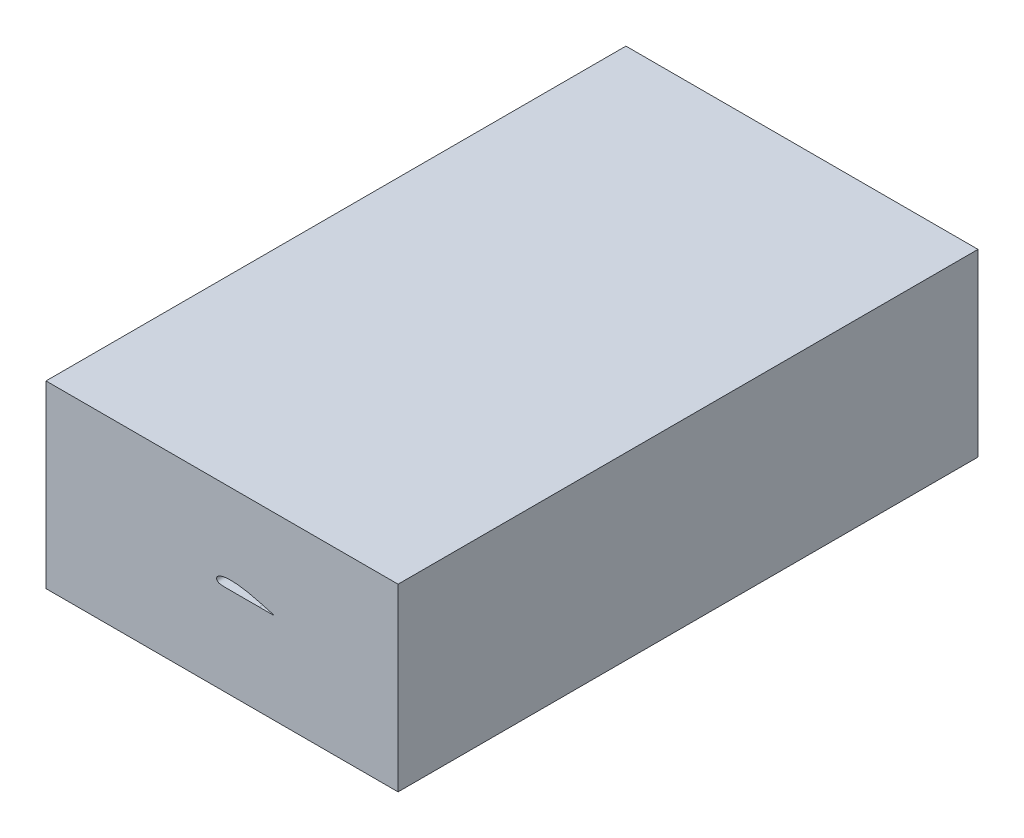
SolidWorks part; units mm, degrees
ref_plane "Front Plane" through (0, 0, 0) normal (0, 0, 1) x (1, 0, 0)
ref_plane "Top Plane" through (0, 0, 0) normal (0, 1, 0) x (1, 0, 0)
ref_plane "Right Plane" through (0, 0, 0) normal (1, 0, 0) x (0, 0, -1)
sketch "Sketch1" plane through (0, 0, 0) normal (0, 0, 1) x (1, 0, 0)
  line L0 (441.3938, 20.1125) -> (470.7202, 20.1125) construction
  line L1 (470.8525, 21.0946) -> (442.557, 28.8563) construction
  line L2 (441.3938, 20.1125) -> (470.7202, 20.1125)
  line L3 (470.8525, 21.0946) -> (442.557, 28.8563)
  line L5 (0, 204.6763) -> (728.5077, 204.6763)
  line L6 (0, 204.6763) -> (0, -167.5714)
  line L7 (0, -167.5714) -> (728.5077, -167.5714)
  line L8 (728.5077, 204.6763) -> (728.5077, -167.5714)
  arc A0 (470.7202, 20.1125) -> (470.8525, 21.0946) centre (470.7202, 20.6125) ccw construction
  arc A1 (470.7202, 20.1125) -> (470.8525, 21.0946) centre (470.7202, 20.6125) ccw
  spline S0 degree 3 poles (1124.9258, 3617.1089) (1623.2842, 17.455) (1021.1685, 21.1727) (419.9315, 20.0736) (410.9894, 20.058) (403.8355, 20.0448) (398.4705, 20.035) (393.1045, 20.0244) (387.735, 20.0177) (383.2749, 20.0094) (379.6961, 19.9964) (376.991, 19.9944) (374.2712, 20.0109) (371.5307, 20.0564) (369.229, 20.1314) (367.3787, 20.22) (365.9782, 20.3046) (364.5787, 20.4101) (363.214, 20.5264) (361.9719, 20.652) (360.9049, 20.8056) (360.0698, 20.9562) (359.288, 21.1303) (358.6401, 21.281) (357.7655, 21.5068) (356.8397, 21.8718) (356.056, 22.2868) (355.3251, 22.8111) (354.7889, 23.3017) (354.3478, 23.793) (353.9982, 24.2624) (353.6956, 24.7529) (353.3653, 25.4506) (353.1116, 26.2983) (352.9613, 27.6499) (353.2277, 28.9329) (353.5863, 29.7672) (353.965, 30.4492) (354.39, 31.0256) (354.8557, 31.5528) (355.3545, 32.0442) (355.8208, 32.4753) (356.5526, 33.1031) (357.3891, 33.7069) (358.2164, 34.2146) (359.2877, 34.7841) (360.5728, 35.3529) (362.0564, 35.8958) (363.4799, 36.3495) (364.9084, 36.7539) (366.8278, 37.2314) (369.2107, 37.707) (372.0662, 38.14) (374.9635, 38.4319) (378.7767, 38.631) (383.377, 38.6454) (388.8653, 38.5359) (394.4128, 38.2045) (401.7202, 37.4887) (410.7798, 36.1975) (421.4868, 34.1106) (594.8285, -5.7248) (705.5133, -179.2585) (3213.2276, 2881.47) knots -10.317793 -10.317793 -10.317793 -10.317793 0.062498 0.124997 0.187495 0.218745 0.249994 0.281243 0.312492 0.343742 0.359366 0.374991 0.390615 0.40624 0.421865 0.429677 0.437489 0.445302 0.453114 0.460926 0.464832 0.468739 0.472645 0.476551 0.480457 0.48241 0.484363 0.486316 0.488269 0.489246 0.490222 0.491199 0.492175 0.493152 0.494129 0.496082 0.497058 0.498035 0.499988 0.501941 0.503894 0.5078 0.511706 0.515612 0.519519 0.523425 0.531237 0.539049 0.546862 0.554674 0.562486 0.578111 0.593736 0.60936 0.624985 0.656234 0.687483 0.718732 0.749982 0.81248 0.874979 0.937477 3.874805 3.874805 3.874805 3.874805 only from (441.3938, 20.1125) to (442.557, 28.8563) construction
  spline S1 degree 3 poles (441.3938, 20.1125) (437.8166, 20.1056) (430.6622, 20.0933) (419.9315, 20.0736) (410.9894, 20.058) (403.8355, 20.0448) (398.4705, 20.035) (393.1045, 20.0244) (387.735, 20.0177) (383.2749, 20.0094) (379.6961, 19.9964) (376.991, 19.9944) (374.2712, 20.0109) (371.5307, 20.0564) (369.229, 20.1314) (367.3787, 20.22) (365.9782, 20.3046) (364.5787, 20.4101) (363.214, 20.5264) (361.9719, 20.652) (360.9049, 20.8056) (360.0698, 20.9562) (359.288, 21.1303) (358.6401, 21.281) (357.7655, 21.5068) (356.8397, 21.8718) (356.056, 22.2868) (355.3251, 22.8111) (354.7889, 23.3017) (354.3478, 23.793) (353.9982, 24.2624) (353.6956, 24.7529) (353.3653, 25.4506) (353.1116, 26.2983) (352.9613, 27.6499) (353.2277, 28.9329) (353.5863, 29.7672) (353.965, 30.4492) (354.39, 31.0256) (354.8557, 31.5528) (355.3545, 32.0442) (355.8208, 32.4753) (356.5526, 33.1031) (357.3891, 33.7069) (358.2164, 34.2146) (359.2877, 34.7841) (360.5728, 35.3529) (362.0564, 35.8958) (363.4799, 36.3495) (364.9084, 36.7539) (366.8278, 37.2314) (369.2107, 37.707) (372.0662, 38.14) (374.9635, 38.4319) (378.7767, 38.631) (383.377, 38.6454) (388.8653, 38.5359) (394.4128, 38.2045) (401.7202, 37.4887) (410.7798, 36.1975) (421.4868, 34.1106) (432.0999, 31.6716) (439.0727, 29.8121) (442.557, 28.8563) knots 0 0 0 0 0.062498 0.124997 0.187495 0.218745 0.249994 0.281243 0.312492 0.343742 0.359366 0.374991 0.390615 0.40624 0.421865 0.429677 0.437489 0.445302 0.453114 0.460926 0.464832 0.468739 0.472645 0.476551 0.480457 0.48241 0.484363 0.486316 0.488269 0.489246 0.490222 0.491199 0.492175 0.493152 0.494129 0.496082 0.497058 0.498035 0.499988 0.501941 0.503894 0.5078 0.511706 0.515612 0.519519 0.523425 0.531237 0.539049 0.546862 0.554674 0.562486 0.578111 0.593736 0.60936 0.624985 0.656234 0.687483 0.718732 0.749982 0.81248 0.874979 0.937477 0.999976 0.999976 0.999976 0.999976
extrude "Boss-Extrude1" add sketch "Sketch1" along normal blind 1200
